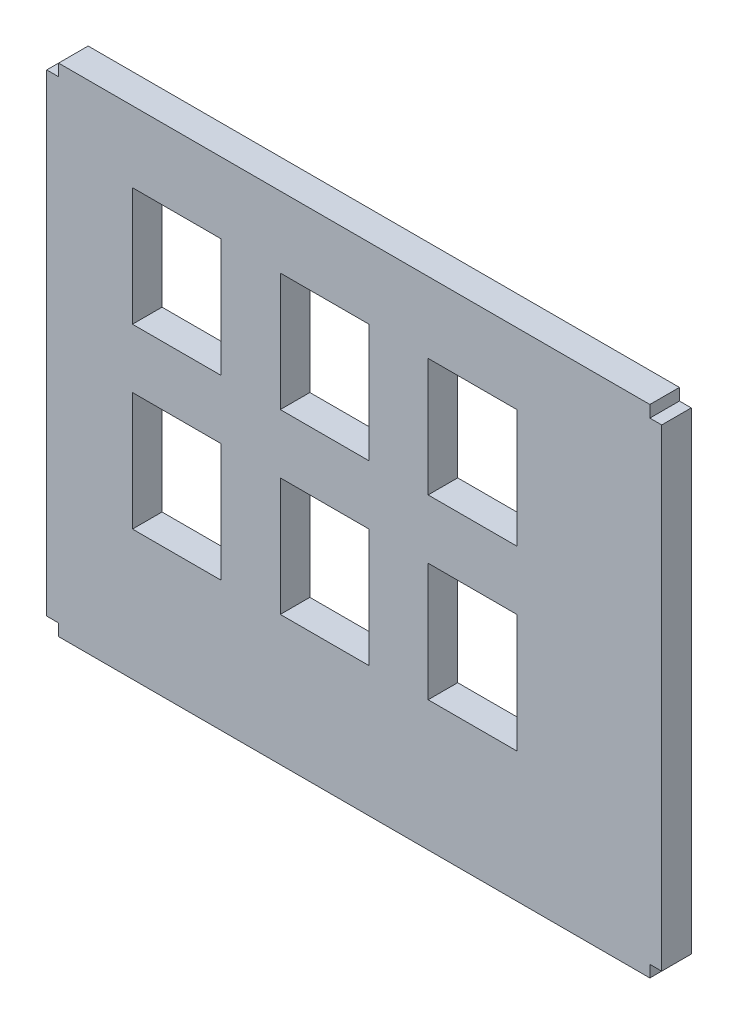
SolidWorks part; units mm, degrees
ref_plane "Ön Düzlem" through (0, 0, 0) normal (0, 0, 1) x (1, 0, 0)
ref_plane "Üst Düzlem" through (0, 0, 0) normal (0, 1, 0) x (1, 0, 0)
ref_plane "Sağ Düzlem" through (0, 0, 0) normal (1, 0, 0) x (0, 0, -1)
sketch "Sketch1" plane through (0, 0, 0) normal (0, 0, 1) x (1, 0, 0)
  line L0 (-54, -43) -> (-54, 37)
  line L1 (-54, 37) -> (-52, 37)
  line L2 (-52, 37) -> (-52, 39)
  line L3 (-52, 39) -> (48, 39)
  line L4 (48, 39) -> (48, 37)
  line L5 (48, 37) -> (50, 37)
  line L6 (50, 37) -> (50, -43)
  line L7 (50, -43) -> (48, -43)
  line L8 (48, -43) -> (48, -45)
  line L9 (48, -45) -> (-52, -45)
  line L10 (-52, -45) -> (-52, -43)
  line L11 (-52, -43) -> (-54, -43)
  line L12 (-14.5, 27) -> (-14.5, 7)
  line L13 (-39.5, 27) -> (-24.5, 27)
  line L14 (-39.5, 27) -> (-39.5, 7)
  line L15 (-39.5, 7) -> (-24.5, 7)
  line L16 (-24.5, 27) -> (-24.5, 7)
  line L17 (-14.5, 27) -> (0.5, 27)
  line L18 (0.5, 27) -> (0.5, 7)
  line L19 (-14.5, 7) -> (0.5, 7)
  line L20 (10.5, 27) -> (10.5, 7)
  line L21 (10.5, 27) -> (25.5, 27)
  line L22 (25.5, 27) -> (25.5, 7)
  line L23 (10.5, 7) -> (25.5, 7)
  line L24 (-14.5, -3) -> (-14.5, -23)
  line L25 (-14.5, -3) -> (0.5, -3)
  line L26 (0.5, -3) -> (0.5, -23)
  line L27 (-14.5, -23) -> (0.5, -23)
  line L28 (10.5, -3) -> (10.5, -23)
  line L29 (10.5, -3) -> (25.5, -3)
  line L30 (25.5, -3) -> (25.5, -23)
  line L31 (10.5, -23) -> (25.5, -23)
  line L32 (-39.5, -3) -> (-39.5, -23)
  line L33 (-39.5, -3) -> (-24.5, -3)
  line L34 (-24.5, -3) -> (-24.5, -23)
  line L35 (-39.5, -23) -> (-24.5, -23)
  dimension "D2" = 100
  dimension "D3" = 80
  dimension "D4" = 45
  dimension "D5" = 2
  dimension "D6" = 50
  dimension "D9" = 15
  dimension "D10" = 20
  dimension "D11" = 3
  dimension "D13" = 12.5
  dimension "D14" = 10
  dimension "D12" = 2
extrude "Boss-Extrude1" add sketch "Sketch1" along normal blind 5
